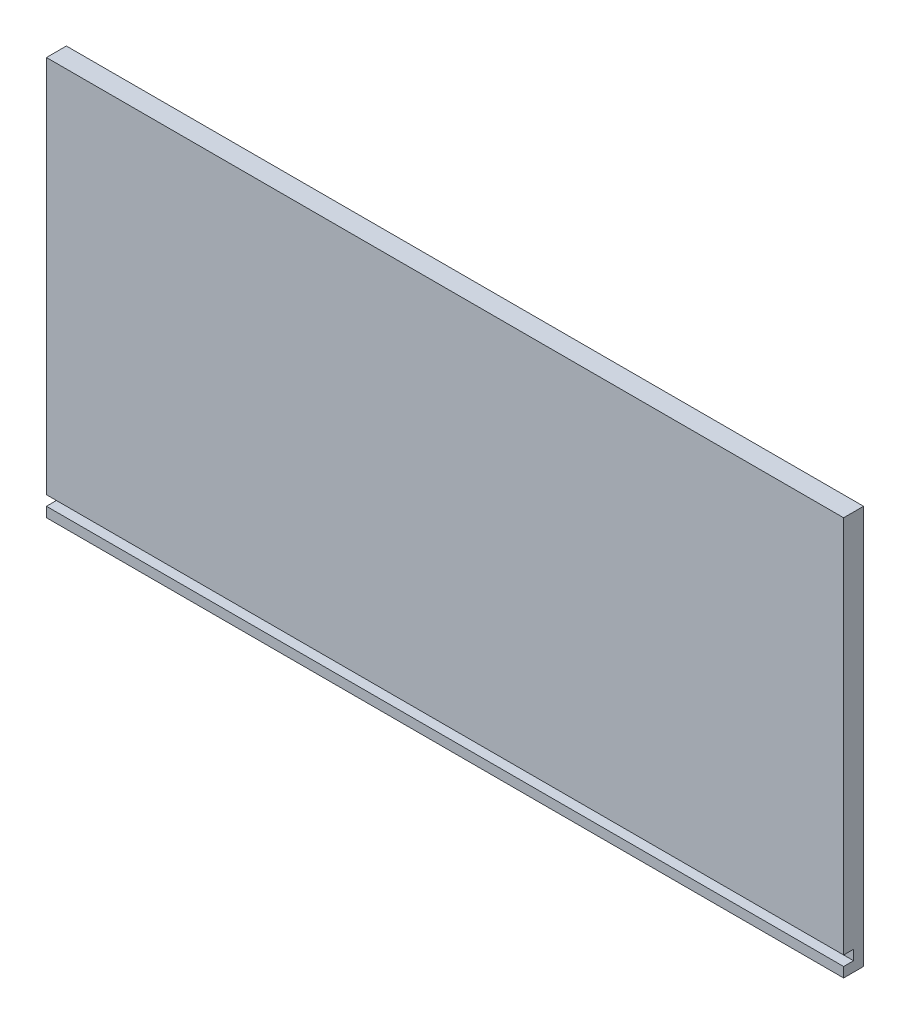
SolidWorks part; units mm, degrees
ref_plane "正面" through (0, 0, 0) normal (0, 0, 1) x (1, 0, 0)
ref_plane "平面" through (0, 0, 0) normal (0, 1, 0) x (1, 0, 0)
ref_plane "右側面" through (0, 0, 0) normal (1, 0, 0) x (0, 0, -1)
sketch "ｽｹｯﾁ1" plane through (0, 0, 0) normal (0, 0, 1) x (1, 0, 0)
  line L1 (-69.2801, 161.5071) -> (330.7199, 161.5071)
  line L2 (-69.2801, 161.5071) -> (-69.2801, -38.4929)
  line L3 (-69.2801, -38.4929) -> (330.7199, -38.4929)
  line L4 (330.7199, 161.5071) -> (330.7199, -38.4929)
  dimension "D1" = 400
  dimension "D3" = 200
extrude "ﾎﾞｽ - 押し出し1" add sketch "ｽｹｯﾁ1" along normal blind 10
sketch "ｽｹｯﾁ2" plane through (0, 0, 10) normal (0, 0, 1) x (1, 0, 0)
  line L0 (330.7199, -38.4929) -> (330.7199, 161.5071) construction
  line L1 (330.7199, -33.4929) -> (-69.2801, -33.4929)
  line L2 (330.7199, -33.4929) -> (330.7199, -28.4929)
  line L3 (330.7199, -28.4929) -> (-69.2801, -28.4929)
  line L4 (-69.2801, -33.4929) -> (-69.2801, -28.4929)
  line L5 (-69.2801, 161.5071) -> (-69.2801, -38.4929) construction
  line L7 (-69.2801, -38.4929) -> (330.7199, -38.4929) construction
  point P10 (0, 0)
  dimension "D1" = 5
  dimension "D2" = 400
  dimension "D3" = 5
extrude "ｶｯﾄ - 押し出し1" cut sketch "ｽｹｯﾁ2" against normal blind 5
